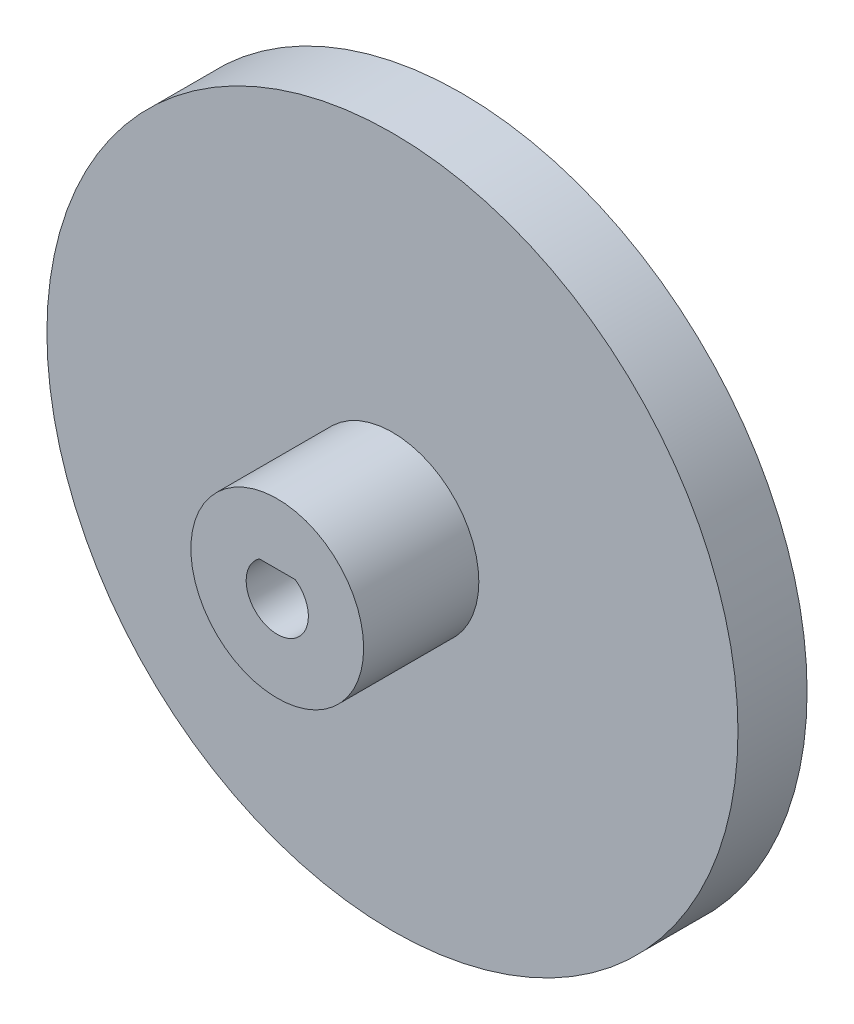
SolidWorks part; units mm, degrees
ref_plane "Front Plane" through (0, 0, 0) normal (0, 0, 1) x (1, 0, 0)
ref_plane "Top Plane" through (0, 0, 0) normal (0, 1, 0) x (1, 0, 0)
ref_plane "Right Plane" through (0, 0, 0) normal (1, 0, 0) x (0, 0, -1)
sketch "Sketch2" plane through (0, 0, 0) normal (0, 0, 1) x (1, 0, 0)
  line L0 (1.5652, 2.2) -> (-1.5652, 2.2)
  line L1 (1.5, 2) -> (-1.5, 2)
  line L2 (1.5, 2) -> (-1.5, 2)
  circle A0 centre (0, 0) radius 11 construction
  arc A1 (-1.5, 2) -> (1.5, 2) centre (0, 0) ccw
  arc A2 (-1.5, 2) -> (1.5, 2) centre (0, 0) ccw
  circle A3 centre (0, 0) radius 11 construction
  circle A4 centre (0, 0) radius 7.5
  arc A5 (-1.5652, 2.2) -> (1.5652, 2.2) centre (0, 0) ccw
  dimension "D2" = 15
  dimension "D1" = 0
  dimension "D3" = 0.2
extrude "Boss-Extrude1" add sketch "Sketch2" against normal blind 10 contours A4 A5 L0
sketch "Sketch4" plane through (0, 0, 0) normal (0, 0, 1) x (1, 0, 0)
  line L0 (0, 30) -> (0, 0) construction
  circle A0 centre (0, 0) radius 30
  circle A1 centre (0, 24) radius 4.25
  circle A2 centre (16.9706, 16.9706) radius 4.25
  circle A3 centre (24, 0) radius 4.25
  circle A4 centre (16.9706, -16.9706) radius 4.25
  circle A5 centre (0, -24) radius 4.25
  circle A6 centre (-16.9706, -16.9706) radius 4.25
  circle A7 centre (-24, 0) radius 4.25
  circle A8 centre (-16.9706, 16.9706) radius 4.25
  point P23 (0, 0)
  dimension "D1" = 8.5
  dimension "D3" = 60
  dimension "D2" = 6
  dimension "D4" = 8
extrude "Boss-Extrude3" add sketch "Sketch4" along normal blind 3
sketch "Sketch5" plane through (0, 0, 3) normal (0, 0, 1) x (1, 0, 0)
  circle A1 centre (0, 0) radius 30
  circle A2 centre (0, 0) radius 30
  dimension "D1" = 0
extrude "Boss-Extrude4" add sketch "Sketch5" along normal blind 3
sketch "Sketch6" plane through (0, 0, 6) normal (0, 0, 1) x (1, 0, 0)
  line L2 (1.5652, 2.2) -> (-1.5652, 2.2) construction
  line L3 (1.5652, 2.2) -> (-1.5652, 2.2)
  circle A4 centre (0, 0) radius 7.5 construction
  circle A5 centre (0, 0) radius 30
  circle A6 centre (0, 0) radius 30
  circle A7 centre (0, 0) radius 7.5
  arc A9 (-1.5652, 2.2) -> (1.5652, 2.2) centre (0, 0) ccw construction
  arc A10 (-1.5652, 2.2) -> (1.5652, 2.2) centre (0, 0) ccw
  dimension "D1" = 0
extrude "Boss-Extrude5" add sketch "Sketch6" along normal blind 10 contours A7 A10 L3 | A6
